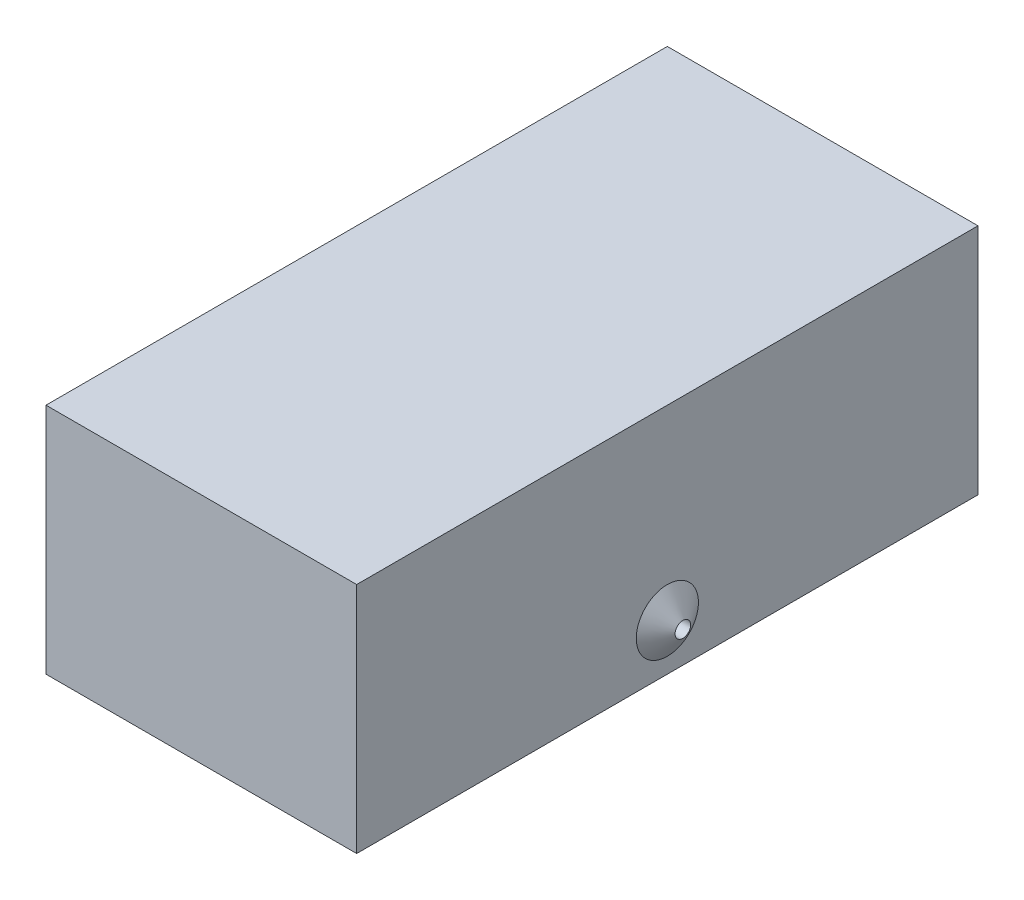
SolidWorks part; units mm, degrees
ref_plane "Front Plane" through (0, 0, 0) normal (0, 0, 1) x (1, 0, 0)
ref_plane "Top Plane" through (0, 0, 0) normal (0, 1, 0) x (1, 0, 0)
ref_plane "Right Plane" through (0, 0, 0) normal (1, 0, 0) x (0, 0, -1)
sketch "Sketch2" plane through (0, 0, 0) normal (0, 1, 0) x (1, 0, 0)
  line L1 (50, -100) -> (-50, -100)
  line L2 (50, -100) -> (50, 100)
  line L3 (50, 100) -> (-50, 100)
  line L4 (-50, -100) -> (-50, 100)
  line L5 (50, -100) -> (-50, 100) construction
  line L6 (50, 100) -> (-50, -100) construction
  point P0 (0, 0)
  dimension "D1" = 100
  dimension "D2" = 200
extrude "Boss-Extrude1" add sketch "Sketch2" along normal blind 75
sketch "Sketch3" plane through (-50, 0, 0) normal (-1, 0, 0) x (0, 0, 1)
  line L0 (0, 75) -> (0, 0) construction
  line L1 (-100, 75) -> (100, 75) construction
  line L2 (-100, 0) -> (100, 0) construction
  line L3 (-100, 37.5) -> (100, 37.5) construction
  line L4 (-100, 75) -> (-100, 0) construction
  line L5 (100, 75) -> (100, 0) construction
  line L6 (55, 0) -> (-55, 0) construction
  circle A0 centre (0, 15) radius 10
  dimension "D1" = 20
  dimension "D2" = 15
ref_plane "Plane1" through (-55, 0, 0) normal (-1, 0, 0) x (0, 0, 1)
sketch "Sketch5" plane through (-55, 0, 0) normal (-1, 0, 0) x (0, 0, 1)
  circle A0 centre (0, 15) radius 2.5
  dimension "D1" = 5
loft "Loft1" add profiles "Sketch5", "Sketch3"
sketch "Sketch6" plane through (-55, 0, 0) normal (-1, 0, 0) x (0, 0, 1)
  line L0 (0, -41.25) -> (0, 41.25) construction
  circle A0 centre (0, 37.5) radius 1.6
  dimension "D1" = 3.2
extrude "Cut-Extrude1" cut sketch "Sketch6" against normal blind 4
mirror "Mirror1" about plane through (0, 0, 0) normal (1, 0, 0) of "Cut-Extrude1", "Loft1"
